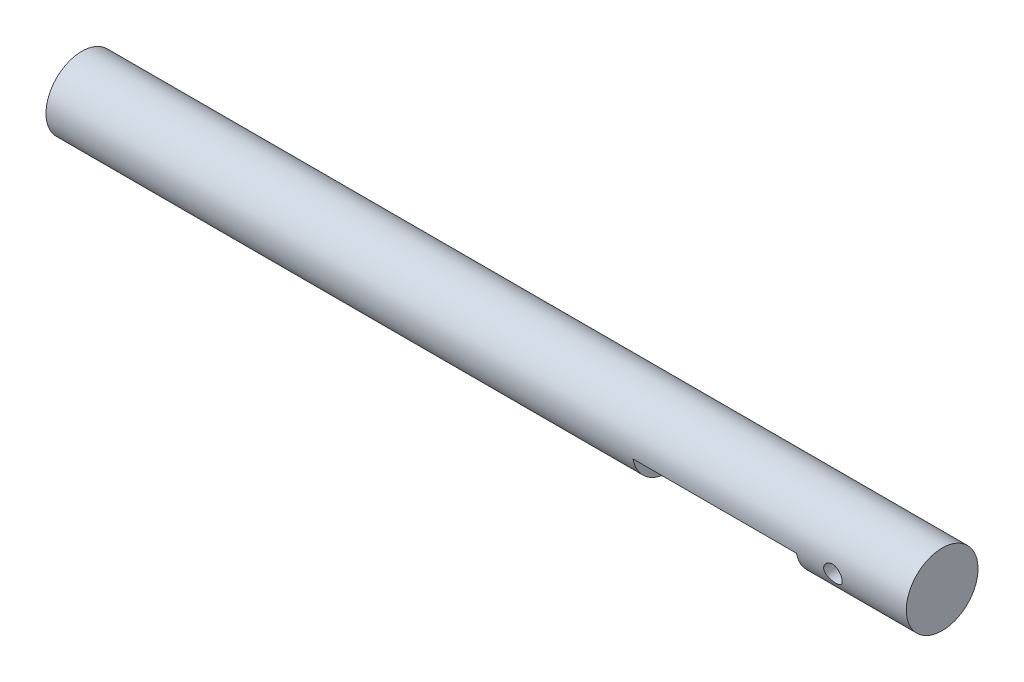
SolidWorks part; units mm, degrees
ref_plane "Front Plane" through (0, 0, 0) normal (0, 0, 1) x (1, 0, 0)
ref_plane "Top Plane" through (0, 0, 0) normal (0, 1, 0) x (1, 0, 0)
ref_plane "Right Plane" through (0, 0, 0) normal (1, 0, 0) x (0, 0, -1)
sketch "Sketch1" plane through (0, 0, 0) normal (0, 0, 1) x (1, 0, 0)
  line L0 (-8.5, -19.85) -> (-8.5, 0)
  line L3 (14.25, 10) -> (-14.25, 10)
  line L4 (-14.25, -19.85) -> (-14.25, 10)
  line L5 (-8.5, 0) -> (8.5, 0)
  line L6 (-14.25, -19.85) -> (-8.5, -19.85)
  line L7 (-8.5, 0) -> (8.5, 0)
  line L8 (0, 10) -> (0, 0)
  line L9 (0, -16.85) -> (0, -17.85)
  line L10 (-8.5, 4) -> (-6.5, 4)
  line L11 (-8.5, 4) -> (-8.5, 6)
  line L12 (-8.5, 6) -> (-6.5, 6)
  line L13 (-6.5, 4) -> (-6.5, 6)
  line L14 (-8.5, 4) -> (-6.5, 6) construction
  line L15 (-8.5, 6) -> (-6.5, 4) construction
  line L20 (8.5, 6) -> (6.5, 4) construction
  line L21 (8.5, 4) -> (6.5, 6) construction
  line L26 (6.5, 4) -> (6.5, 6)
  line L27 (8.5, 6) -> (6.5, 6)
  line L28 (8.5, 4) -> (8.5, 6)
  line L29 (8.5, 4) -> (6.5, 4)
  line L31 (14.25, -19.85) -> (8.5, -19.85)
  line L32 (14.25, -19.85) -> (14.25, 10)
  line L33 (8.5, -19.85) -> (8.5, 0)
  circle A0 centre (-7.5, 5) radius 1
  circle A3 centre (7.5, 5) radius 1
  circle A4 centre (-11.375, -17.35) radius 0.5
  circle A6 centre (11.375, -17.35) radius 0.5
  point P18 (-11.375, -16.85)
  point P19 (-11.375, -16.85)
  point P20 (0, -16.85)
  point P25 (-11.375, -17.85)
  dimension "D5" = 2
  dimension "D10" = 2.5
  dimension "D8" = 1
  dimension "D11" = 2.875
  dimension "D1" = 29.85
  dimension "D2" = 14.25
  dimension "D3" = 10
  dimension "D4" = 5.75
  dimension "D6" = 4
  dimension "D7" = 5.75
extrude "Boss-Extrude1" add sketch "Sketch1" along normal mid plane 3
sketch "Sketch2" plane through (0, 0, 1.5) normal (0, 0, 1) x (1, 0, 0)
  line L0 (-8.5, -19.85) -> (-8.5, 0) construction
  line L1 (-14.25, -19.85) -> (-8.5, -19.85)
  line L2 (-14.25, -19.85) -> (-14.25, -15.85)
  line L3 (-14.25, -15.85) -> (-8.5, -15.85)
  line L4 (-8.5, -19.85) -> (-8.5, -15.85)
  line L5 (0, -15.85) -> (0, -19.85)
  line L6 (14.25, -15.85) -> (8.5, -15.85)
  line L7 (8.5, -19.85) -> (8.5, -15.85)
  line L8 (14.25, -19.85) -> (8.5, -19.85)
  line L9 (14.25, -19.85) -> (14.25, -15.85)
  dimension "D1" = 4
extrude "Cut-Extrude1" cut sketch "Sketch2" against normal blind 1
sketch "Sketch5" plane through (0, 0, 0) normal (1, 0, 0) x (0, 0, -1)
  circle A0 centre (0, 6.25) radius 6.25
  point P0 (0, 0)
  dimension "D1" = 12.5
extrude "Boss-Extrude2" add sketch "Sketch5" against normal blind 125 and the other way blind 25 from surface at 8.5 starting at face at (8.5, -11.9, 0.1667)
sketch "Sketch6" plane through (0, -19.85, 0) normal (0, -1, 0) x (1, 0, 0)
  line L0 (14.25, -1.5) -> (14.25, 1.5) construction
  line L1 (-14.25, -6.25) -> (14.25, -6.25)
  line L2 (-14.25, -6.25) -> (-14.25, 6.25)
  line L3 (-14.25, 6.25) -> (14.25, 6.25)
  line L4 (14.25, -6.25) -> (14.25, 6.25)
  line L5 (-14.25, -6.25) -> (14.25, 6.25) construction
  line L6 (-14.25, 6.25) -> (14.25, -6.25) construction
  line L7 (33.5, 6.25) -> (-116.5, 6.25) construction
  point P0 (0, 0)
extrude "Cut-Extrude2" cut sketch "Sketch6" against normal blind 25
sketch "Sketch7" plane through (0, 5.15, 0) normal (0, -1, 0) x (-1, 0, 0)
  line L0 (-33.5, -6.25) -> (116.5, -6.25) construction
  circle A0 centre (7.5, 0) radius 1.25
  circle A1 centre (-7.5, 0) radius 1.25
  dimension "D1" = 15
  dimension "D2" = 2.5
  dimension "D3" = 7.5
  dimension "D4" = 6.25
  dimension "D5" = 7.5
extrude "Cut-Extrude3" cut sketch "Sketch7" against normal blind 3.175
sketch "Sketch8" plane through (0, 0, 0) normal (0, 0, 1) x (1, 0, 0)
  line L1 (-14.25, 5.15) -> (14.25, 5.15)
  circle A0 centre (20.6, 5.15) radius 1.5875
  dimension "D1" = 3.175
  dimension "D2" = 6.35
extrude "Cut-Extrude4" cut sketch "Sketch8" along normal up to surface (6.1524 mm away) contours A0
